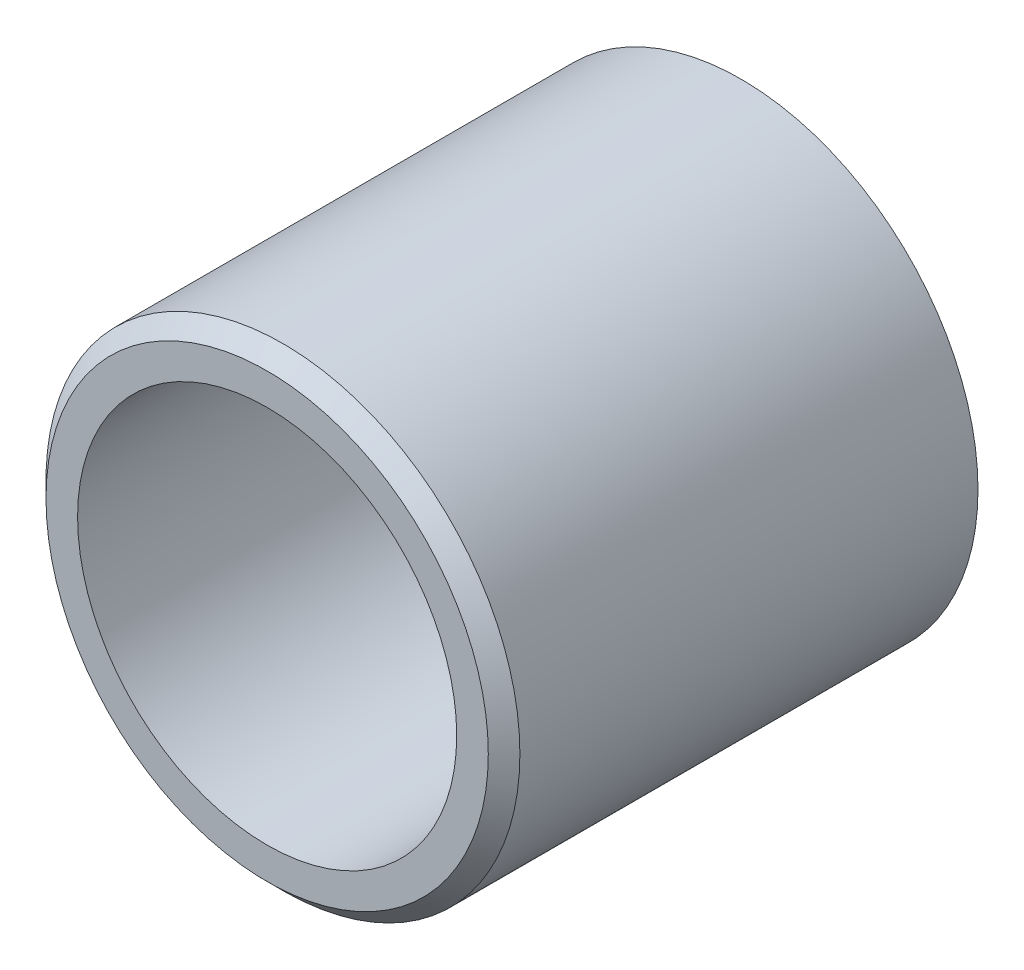
SolidWorks part; units mm, degrees
ref_plane "Front Plane" through (0, 0, 0) normal (0, 0, 1) x (1, 0, 0)
ref_plane "Top Plane" through (0, 0, 0) normal (0, 1, 0) x (1, 0, 0)
ref_plane "Right Plane" through (0, 0, 0) normal (1, 0, 0) x (0, 0, -1)
sketch "Sketch1" plane through (0, 0, 0) normal (0, 0, 1) x (1, 0, 0)
  circle A0 centre (0, 0) radius 7.5
  circle A1 centre (0, 0) radius 6
  dimension "D1" = 15
  dimension "D2" = 12
extrude "Boss-Extrude1" add sketch "Sketch1" along normal blind 15
chamfer "Chamfer1" distance 0.5 angle 45 1 edges at (7.5, 0, 15)
